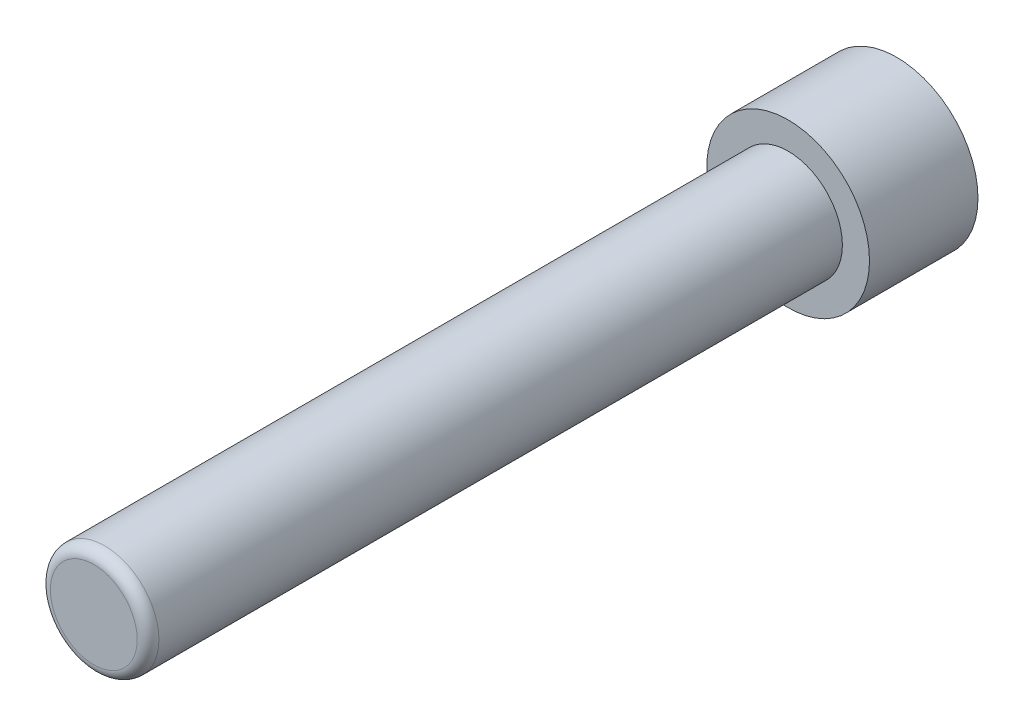
SolidWorks part; units mm, degrees
material "Plain Carbon Steel"
ref_plane "Front Plane" through (0, 0, 0) normal (0, 0, 1) x (1, 0, 0)
ref_plane "Top Plane" through (0, 0, 0) normal (0, 1, 0) x (1, 0, 0)
ref_plane "Right Plane" through (0, 0, 0) normal (1, 0, 0) x (0, 0, -1)
sketch "Sketch1" plane through (0, 0, 0) normal (0, 0, 1) x (1, 0, 0)
  line L0 (0, 0) -> (0, 8.2431) construction
  line L1 (1.905, 1.0999) -> (0, 2.1997)
  line L2 (0, 2.1997) -> (-1.905, 1.0999)
  line L3 (-1.905, 1.0999) -> (-1.905, -1.0999)
  line L4 (-1.905, -1.0999) -> (0, -2.1997)
  line L5 (0, -2.1997) -> (1.905, -1.0999)
  line L6 (1.905, -1.0999) -> (1.905, 1.0999)
  circle A0 centre (0, 0) radius 1.905 construction
  circle A1 centre (0, 0) radius 3.81
  dimension "D1" = 3.81
  dimension "D2" = 7.62
extrude "Boss-Extrude1" add sketch "Sketch1" along normal blind 5.08
sketch "Sketch2" plane through (0, 0, 5.08) normal (0, 0, 1) x (1, 0, 0)
  circle A0 centre (0, 0) radius 2.54
  dimension "D1" = 5.08
extrude "Boss-Extrude2" add sketch "Sketch2" along normal blind 32.512
fillet "Fillet1" radius 0.508 1 edges at (2.54, 0, 37.592)
